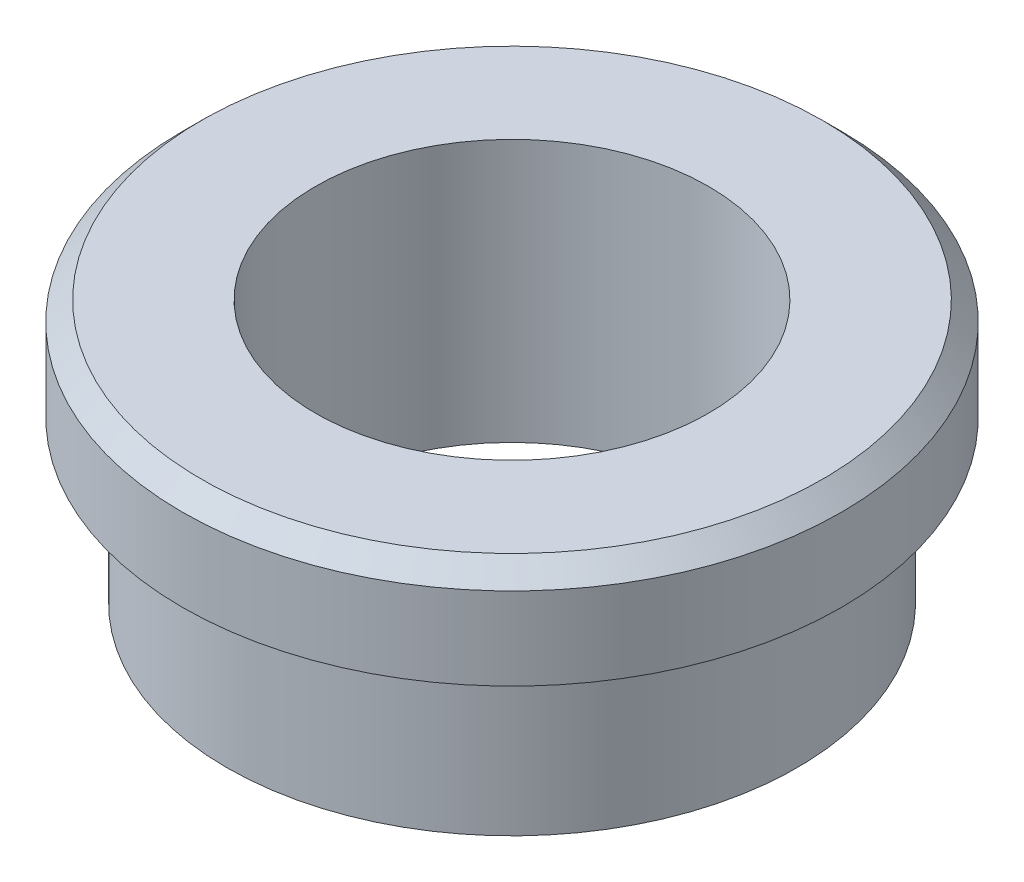
SolidWorks part; units mm, degrees
material "AISI 1020"
ref_plane "Plano frontal" through (0, 0, 0) normal (0, 0, 1) x (1, 0, 0)
ref_plane "Plano superior" through (0, 0, 0) normal (0, 1, 0) x (1, 0, 0)
ref_plane "Plano direito" through (0, 0, 0) normal (1, 0, 0) x (0, 0, -1)
sketch "Esboço1" plane through (0, 0, 0) normal (0, 0, 1) x (1, 0, 0)
  line L0 (0, 0) -> (0, 20.7) construction
  line L1 (15.5, 0) -> (15.5, 20.7)
  line L2 (15.5, 20.7) -> (24.5, 20.7)
  line L3 (26, 19.2) -> (26, 12.7)
  line L4 (26, 12.7) -> (22.5, 12.7)
  line L5 (22.5, 12.7) -> (22.5, 0)
  line L6 (22.5, 0) -> (15.5, 0)
  line L7 (24.5, 20.7) -> (26, 19.2)
  point P6 (26, 20.7)
  dimension "D1" = 31
  dimension "D2" = 52
  dimension "D3" = 8
  dimension "D4" = 45
  dimension "D5" = 20.7
revolve "Revolução1" add sketch "Esboço1" angle 360 about L0
